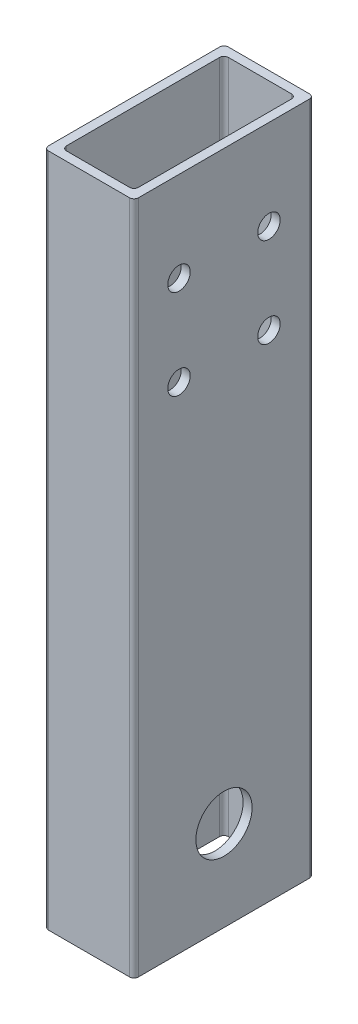
SolidWorks part; units mm, degrees
ref_plane "Plan de face" through (0, 0, 0) normal (0, 0, 1) x (1, 0, 0)
ref_plane "Plan de dessus" through (0, 0, 0) normal (0, 1, 0) x (1, 0, 0)
ref_plane "Plan de droite" through (0, 0, 0) normal (1, 0, 0) x (0, 0, -1)
sketch "Esquisse2" plane through (0, 0, 0) normal (0, 1, 0) x (1, 0, 0)
  line L0 (6, 4) -> (34, 4)
  line L1 (2, 0) -> (38, 0)
  line L2 (0, 2) -> (0, 78)
  line L3 (2, 80) -> (38, 80)
  line L4 (40, 2) -> (40, 78)
  line L5 (36, 6) -> (36, 74)
  line L6 (6, 76) -> (34, 76)
  line L7 (4, 6) -> (4, 74)
  line L8 (4, 4) -> (36, 4) construction
  line L9 (36, 4) -> (36, 76) construction
  line L10 (4, 76) -> (36, 76) construction
  line L11 (4, 4) -> (4, 76) construction
  line L12 (0, 0) -> (40, 0) construction
  line L13 (0, 0) -> (0, 80) construction
  line L14 (0, 80) -> (40, 80) construction
  line L15 (40, 0) -> (40, 80) construction
  arc A0 (34, 4) -> (36, 6) centre (34, 6) ccw
  arc A1 (36, 74) -> (34, 76) centre (34, 74) ccw
  arc A2 (6, 76) -> (4, 74) centre (6, 74) ccw
  arc A3 (4, 6) -> (6, 4) centre (6, 6) ccw
  arc A4 (2, 0) -> (0, 2) centre (2, 2) cw
  arc A5 (0, 78) -> (2, 80) centre (2, 78) cw
  arc A6 (38, 80) -> (40, 78) centre (38, 78) cw
  arc A7 (40, 2) -> (38, 0) centre (38, 2) cw
  point P24 (0, 0)
  dimension "D4" = 2
  dimension "D1" = 80
  dimension "D2" = 40
  dimension "D3" = 4
extrude "Boss.-Extru.1" add sketch "Esquisse2" along normal blind 300
sketch "Esquisse3" plane through (40, 0, 0) normal (1, 0, 0) x (0, 0, -1)
  line L0 (80, 40) -> (40, 40) construction
  line L1 (40, 40) -> (40, 0) construction
  line L4 (2, 0) -> (78, 0) construction
  line L5 (80, 300) -> (80, 0) construction
  circle A0 centre (40, 40) radius 12.5
  dimension "D1" = 25
  dimension "D2" = 40
extrude "Enlèv. mat.-Extru.1" cut sketch "Esquisse3" against normal through all
sketch "Esquisse4" plane through (40, 0, 0) normal (1, 0, 0) x (0, 0, -1)
  line L0 (40, 40) -> (40, 240) construction
  line L1 (40, 240) -> (140, 240) construction
  line L3 (60, 260) -> (20, 260) construction
  line L4 (20, 260) -> (20, 220) construction
  circle A0 centre (60, 220) radius 5
  circle A1 centre (20, 220) radius 5
  circle A2 centre (20, 260) radius 5
  circle A3 centre (60, 260) radius 5
  dimension "D5" = 10
  dimension "D9" = 20
  dimension "D1" = 200
  dimension "D2" = 100
  dimension "D3" = 20
  dimension "D4" = 20
  dimension "D8" = 20
  dimension "D6" = 2
  dimension "D7" = 2
extrude "Enlèv. mat.-Extru.2" cut sketch "Esquisse4" against normal through all
